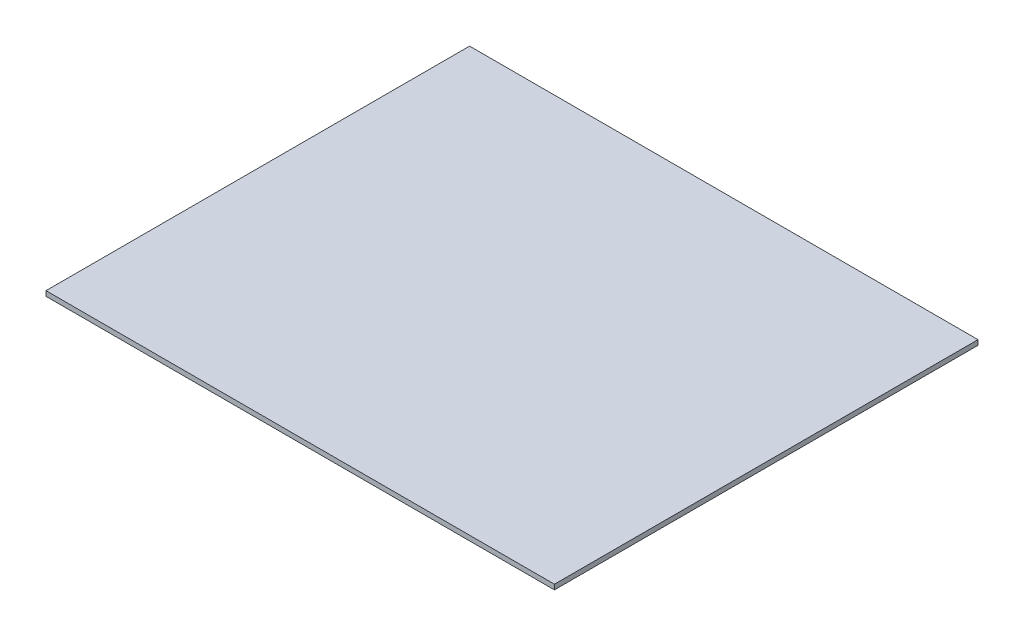
SolidWorks part; units mm, degrees
ref_plane "Спереди" through (0, 0, 0) normal (0, 0, 1) x (1, 0, 0)
ref_plane "Сверху" through (0, 0, 0) normal (0, 1, 0) x (1, 0, 0)
ref_plane "Справа" through (0, 0, 0) normal (1, 0, 0) x (0, 0, -1)
sketch "Эскиз1" plane through (0, 0, 0) normal (0, 1, 0) x (1, 0, 0)
  line L0 (0, -88.8935) -> (246.7048, -88.8935) construction
  line L1 (3.8526, -9.8935) -> (209.8526, -9.8935)
  line L2 (3.8526, -9.8935) -> (3.8526, -181.5135)
  line L3 (3.8526, -181.5135) -> (209.8526, -181.5135)
  line L4 (209.8526, -9.8935) -> (209.8526, -181.5135)
extrude "Вытянуть1" add sketch "Эскиз1" along normal blind 2
